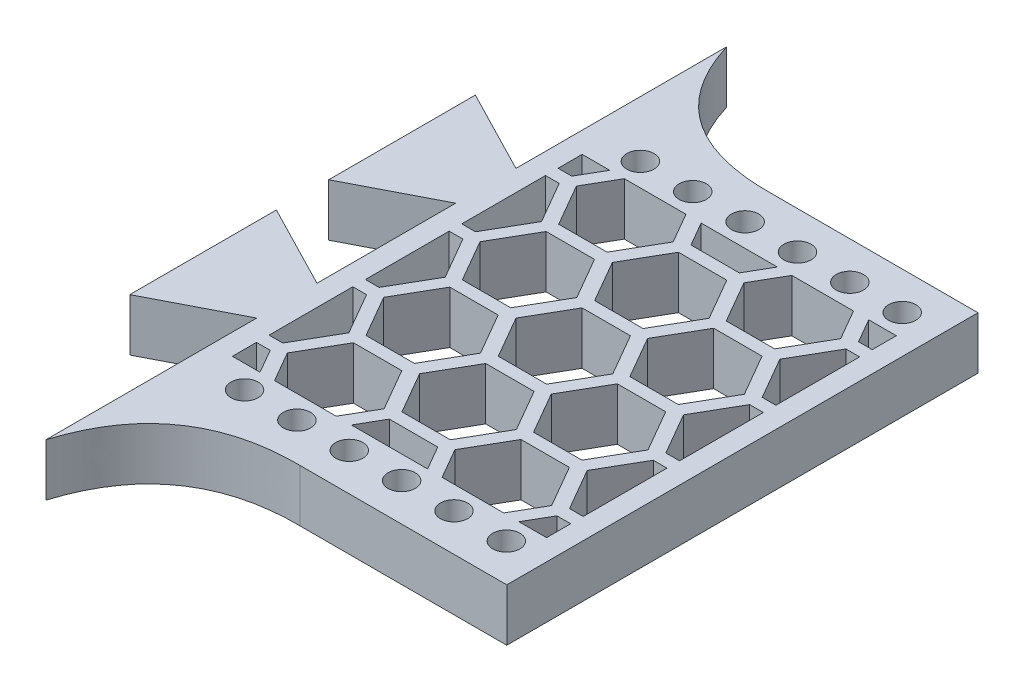
SolidWorks part; units mm, degrees
material "ABS PC"
ref_plane "Front Plane" through (0, 0, 0) normal (0, 0, 1) x (1, 0, 0)
ref_plane "Top Plane" through (0, 0, 0) normal (0, 1, 0) x (1, 0, 0)
ref_plane "Right Plane" through (0, 0, 0) normal (1, 0, 0) x (0, 0, -1)
sketch "Sketch1" plane through (0, 0, 0) normal (0, 1, 0) x (1, 0, 0)
  line L0 (-21.59, -15.7187) -> (-31.75, -20.955)
  line L1 (21.59, -28.575) -> (-21.59, -28.575)
  line L2 (21.59, -28.575) -> (21.59, 28.575)
  line L3 (21.59, 28.575) -> (-21.59, 28.575)
  line L4 (-21.59, -28.575) -> (-21.59, 28.575)
  line L5 (21.59, -28.575) -> (-21.59, 28.575) construction
  line L6 (21.59, 28.575) -> (-21.59, -28.575) construction
  line L7 (-31.75, -20.955) -> (-31.75, -3.175)
  line L8 (-31.75, -3.175) -> (-21.59, -8.4113)
  line L9 (-21.59, 8.4113) -> (-31.75, 3.175)
  line L10 (-31.75, 3.175) -> (-31.75, 20.955)
  line L11 (-31.75, 20.955) -> (-21.59, 15.7187)
  line L12 (-21.59, 15.7187) -> (0, 0) construction
  line L13 (0, 0) -> (-21.59, -15.7187) construction
  line L14 (0, 0) -> (-31.75, 3.175) construction
  line L15 (-31.75, -3.175) -> (0, 0) construction
  line L16 (-21.59, -28.575) -> (-21.59, -41.275)
  line L18 (-21.59, -28.575) -> (-10.9458, -36.6173) construction
  line L19 (0, 0) -> (21.59, 0) construction
  line L20 (-21.59, 28.575) -> (-21.59, 41.275)
  spline S0 degree 2 poles (-21.59, -41.275) (-17.6152, -28.3979) (-3.4579, -28.575) knots 0 0 0 1 1 1
  spline S1 degree 2 poles (-21.59, 41.275) (-17.6152, 28.3979) (-3.4579, 28.575) knots 0 0 0 1 1 1
  point P0 (0, 0)
  point P22 (0, 0)
  point P24 (0, 0)
  point P25 (-3.3106, -29.6861)
  point P26 (0, 0)
  point P27 (-17.0157, -32.0311)
  point P28 (-7.5052, -28.575)
  point P29 (-10.9458, -36.6173)
  point P30 (-6.1522, -28.575)
  point P31 (-3.4579, -28.575)
  dimension "D1" = 57.15
  dimension "D2" = 43.18
  dimension "D3" = 17.78
  dimension "D4" = 11.43
  dimension "D5" = 10.16
  dimension "D6" = 6.35
  dimension "D7" = 12.7
extrude "Boss-Extrude1" add sketch "Sketch1" along normal blind 6.35 contours L8 L7 L0 L4 | L4 L1 L2 L3 | L11 L10 L9 L4 | L16 S0 L1 | S1 L20 L3
sketch "Sketch2" plane through (0, 6.35, 0) normal (0, 1, 0) x (1, 0, 0)
  line L0 (21.59, -28.575) -> (21.59, 28.575) construction
  line L1 (21.59, 28.575) -> (-3.4579, 28.575) construction
  line L2 (21.59, -28.575) -> (-3.4579, -28.575) construction
  circle A0 centre (4.2672, 24.003) radius 1.651
  circle A1 centre (4.2672, -24.003) radius 1.651
  circle A2 centre (10.6172, 24.003) radius 1.651
  circle A3 centre (10.6172, -24.003) radius 1.651
  circle A4 centre (16.9672, 24.003) radius 1.651
  circle A5 centre (16.9672, -24.003) radius 1.651
  circle A6 centre (-2.0828, 24.003) radius 1.651
  circle A7 centre (-2.0828, -24.003) radius 1.651
  circle A8 centre (-8.4328, 24.003) radius 1.651
  circle A9 centre (-8.4328, -24.003) radius 1.651
  circle A10 centre (-14.7828, 24.003) radius 1.651
  circle A11 centre (-14.7828, -24.003) radius 1.651
  dimension "D1" = 17.3228
  dimension "D2" = 17.3228
  dimension "D3" = 4.572
  dimension "D4" = 4.572
  dimension "D5" = 3.302
  dimension "D6" = 3
  dimension "D7" = 4
extrude "Cut-Extrude1" cut sketch "Sketch2" against normal through all
sketch "Sketch3" plane through (0, 6.35, 0) normal (0, 1, 0) x (1, 0, 0)
  line L0 (26.1859, 0) -> (23.2529, 5.08)
  line L1 (5.8659, 0) -> (2.9329, 5.08)
  line L2 (2.9329, 5.08) -> (-2.9329, 5.08)
  line L3 (-2.9329, 5.08) -> (-5.8659, 0)
  line L4 (-5.8659, 0) -> (-2.9329, -5.08)
  line L5 (-2.9329, -5.08) -> (2.9329, -5.08)
  line L6 (2.9329, -5.08) -> (5.8659, 0)
  line L7 (23.2529, 5.08) -> (17.3871, 5.08)
  line L8 (17.3871, 5.08) -> (14.4541, 0)
  line L9 (14.4541, 0) -> (17.3871, -5.08)
  line L10 (17.3871, -5.08) -> (23.2529, -5.08)
  line L11 (23.2529, -5.08) -> (26.1859, 0)
  line L12 (26.1859, 11.684) -> (23.2529, 16.764)
  line L13 (23.2529, 16.764) -> (17.3871, 16.764)
  line L14 (17.3871, 16.764) -> (14.4541, 11.684)
  line L15 (14.4541, 11.684) -> (17.3871, 6.604)
  line L16 (17.3871, 6.604) -> (23.2529, 6.604)
  line L17 (23.2529, 6.604) -> (26.1859, 11.684)
  line L18 (26.1859, 23.368) -> (23.2529, 28.448)
  line L19 (23.2529, 28.448) -> (17.3871, 28.448)
  line L20 (17.3871, 28.448) -> (14.4541, 23.368)
  line L21 (14.4541, 23.368) -> (17.3871, 18.288)
  line L22 (17.3871, 18.288) -> (23.2529, 18.288)
  line L23 (23.2529, 18.288) -> (26.1859, 23.368)
  line L24 (5.8659, 11.684) -> (2.9329, 16.764)
  line L25 (2.9329, 16.764) -> (-2.9329, 16.764)
  line L26 (-2.9329, 16.764) -> (-5.8659, 11.684)
  line L27 (-5.8659, 11.684) -> (-2.9329, 6.604)
  line L28 (-2.9329, 6.604) -> (2.9329, 6.604)
  line L29 (2.9329, 6.604) -> (5.8659, 11.684)
  line L30 (5.8659, 23.368) -> (2.9329, 28.448)
  line L31 (2.9329, 28.448) -> (-2.9329, 28.448)
  line L32 (-2.9329, 28.448) -> (-5.8659, 23.368)
  line L33 (-5.8659, 23.368) -> (-2.9329, 18.288)
  line L34 (-2.9329, 18.288) -> (2.9329, 18.288)
  line L35 (2.9329, 18.288) -> (5.8659, 23.368)
  line L36 (-14.4541, 0) -> (-17.3871, 5.08)
  line L37 (-17.3871, 5.08) -> (-23.2529, 5.08)
  line L38 (-23.2529, 5.08) -> (-26.1859, 0)
  line L39 (-26.1859, 0) -> (-23.2529, -5.08)
  line L40 (-23.2529, -5.08) -> (-17.3871, -5.08)
  line L41 (-17.3871, -5.08) -> (-14.4541, 0)
  line L42 (-14.4541, -11.684) -> (-17.3871, -6.604)
  line L43 (-17.3871, -6.604) -> (-23.2529, -6.604)
  line L44 (-23.2529, -6.604) -> (-26.1859, -11.684)
  line L45 (-26.1859, -11.684) -> (-23.2529, -16.764)
  line L46 (-23.2529, -16.764) -> (-17.3871, -16.764)
  line L47 (-17.3871, -16.764) -> (-14.4541, -11.684)
  line L48 (-14.4541, -23.368) -> (-17.3871, -18.288)
  line L49 (-17.3871, -18.288) -> (-23.2529, -18.288)
  line L50 (-23.2529, -18.288) -> (-26.1859, -23.368)
  line L51 (-26.1859, -23.368) -> (-23.2529, -28.448)
  line L52 (-23.2529, -28.448) -> (-17.3871, -28.448)
  line L53 (-17.3871, -28.448) -> (-14.4541, -23.368)
  line L54 (5.8659, -11.684) -> (2.9329, -6.604)
  line L55 (2.9329, -6.604) -> (-2.9329, -6.604)
  line L56 (-2.9329, -6.604) -> (-5.8659, -11.684)
  line L57 (-5.8659, -11.684) -> (-2.9329, -16.764)
  line L58 (-2.9329, -16.764) -> (2.9329, -16.764)
  line L59 (2.9329, -16.764) -> (5.8659, -11.684)
  line L60 (5.8659, -23.368) -> (2.9329, -18.288)
  line L61 (2.9329, -18.288) -> (-2.9329, -18.288)
  line L62 (-2.9329, -18.288) -> (-5.8659, -23.368)
  line L63 (-5.8659, -23.368) -> (-2.9329, -28.448)
  line L64 (-2.9329, -28.448) -> (2.9329, -28.448)
  line L65 (2.9329, -28.448) -> (5.8659, -23.368)
  line L66 (-14.4541, 11.684) -> (-17.3871, 16.764)
  line L67 (-17.3871, 16.764) -> (-23.2529, 16.764)
  line L68 (-23.2529, 16.764) -> (-26.1859, 11.684)
  line L69 (-26.1859, 11.684) -> (-23.2529, 6.604)
  line L70 (-23.2529, 6.604) -> (-17.3871, 6.604)
  line L71 (-17.3871, 6.604) -> (-14.4541, 11.684)
  line L72 (-14.4541, 23.368) -> (-17.3871, 28.448)
  line L73 (-17.3871, 28.448) -> (-23.2529, 28.448)
  line L74 (-23.2529, 28.448) -> (-26.1859, 23.368)
  line L75 (-26.1859, 23.368) -> (-23.2529, 18.288)
  line L76 (-23.2529, 18.288) -> (-17.3871, 18.288)
  line L77 (-17.3871, 18.288) -> (-14.4541, 23.368)
  line L78 (26.1859, -11.684) -> (23.2529, -6.604)
  line L79 (15.9845, -17.526) -> (13.0516, -12.446)
  line L80 (13.0516, -12.446) -> (7.1857, -12.446)
  line L81 (7.1857, -12.446) -> (4.2528, -17.526)
  line L82 (4.2528, -17.526) -> (7.1857, -22.606)
  line L83 (7.1857, -22.606) -> (13.0516, -22.606)
  line L84 (13.0516, -22.606) -> (15.9845, -17.526)
  line L85 (23.2529, -6.604) -> (17.3871, -6.604)
  line L86 (17.3871, -6.604) -> (14.4541, -11.684)
  line L87 (14.4541, -11.684) -> (17.3871, -16.764)
  line L88 (17.3871, -16.764) -> (23.2529, -16.764)
  line L89 (23.2529, -16.764) -> (26.1859, -11.684)
  line L90 (26.1859, -23.368) -> (23.2529, -18.288)
  line L91 (23.2529, -18.288) -> (17.3871, -18.288)
  line L92 (17.3871, -18.288) -> (14.4541, -23.368)
  line L93 (14.4541, -23.368) -> (17.3871, -28.448)
  line L94 (17.3871, -28.448) -> (23.2529, -28.448)
  line L95 (23.2529, -28.448) -> (26.1859, -23.368)
  line L96 (-4.3355, -17.526) -> (-7.2684, -12.446)
  line L97 (-13.1343, -12.446) -> (-16.0672, -17.526)
  line L98 (-16.0672, -17.526) -> (-13.1343, -22.606)
  line L99 (-7.2684, -22.606) -> (-4.3355, -17.526)
  line L100 (-7.2684, -12.446) -> (-13.1343, -12.446)
  line L101 (-13.1343, -22.606) -> (-7.2684, -22.606)
  line L102 (-4.3355, -5.842) -> (-7.2684, -0.762)
  line L103 (-13.1343, -0.762) -> (-16.0672, -5.842)
  line L104 (-16.0672, -5.842) -> (-13.1343, -10.922)
  line L105 (-7.2684, -10.922) -> (-4.3355, -5.842)
  line L106 (-7.2684, -0.762) -> (-13.1343, -0.762)
  line L107 (-13.1343, -10.922) -> (-7.2684, -10.922)
  line L108 (-4.3355, 5.842) -> (-7.2684, 10.922)
  line L109 (-13.1343, 10.922) -> (-16.0672, 5.842)
  line L110 (-16.0672, 5.842) -> (-13.1343, 0.762)
  line L111 (-7.2684, 0.762) -> (-4.3355, 5.842)
  line L112 (-7.2684, 10.922) -> (-13.1343, 10.922)
  line L113 (-13.1343, 0.762) -> (-7.2684, 0.762)
  line L114 (-4.3355, 17.526) -> (-7.2684, 22.606)
  line L115 (-13.1343, 22.606) -> (-16.0672, 17.526)
  line L116 (-16.0672, 17.526) -> (-13.1343, 12.446)
  line L117 (-7.2684, 12.446) -> (-4.3355, 17.526)
  line L118 (-7.2684, 22.606) -> (-13.1343, 22.606)
  line L119 (-13.1343, 12.446) -> (-7.2684, 12.446)
  line L120 (15.9845, -5.842) -> (13.0516, -0.762)
  line L121 (7.1857, -0.762) -> (4.2528, -5.842)
  line L122 (4.2528, -5.842) -> (7.1857, -10.922)
  line L123 (13.0516, -10.922) -> (15.9845, -5.842)
  line L124 (13.0516, -0.762) -> (7.1857, -0.762)
  line L125 (7.1857, -10.922) -> (13.0516, -10.922)
  line L126 (15.9845, 5.842) -> (13.0516, 10.922)
  line L127 (7.1857, 10.922) -> (4.2528, 5.842)
  line L128 (4.2528, 5.842) -> (7.1857, 0.762)
  line L129 (13.0516, 0.762) -> (15.9845, 5.842)
  line L130 (13.0516, 10.922) -> (7.1857, 10.922)
  line L131 (7.1857, 0.762) -> (13.0516, 0.762)
  line L132 (15.9845, 17.526) -> (13.0516, 22.606)
  line L133 (7.1857, 22.606) -> (4.2528, 17.526)
  line L134 (4.2528, 17.526) -> (7.1857, 12.446)
  line L135 (13.0516, 12.446) -> (15.9845, 17.526)
  line L136 (13.0516, 22.606) -> (7.1857, 22.606)
  line L137 (7.1857, 12.446) -> (13.0516, 12.446)
  line L138 (-19.05, 21.209) -> (19.05, 21.209)
  line L139 (19.05, 21.209) -> (19.05, -21.209)
  line L140 (19.05, -21.209) -> (-19.05, -21.209)
  line L141 (-19.05, -21.209) -> (-19.05, 21.209)
  line L142 (-21.59, 15.7187) -> (-21.59, 41.275) construction
  line L143 (21.59, -28.575) -> (21.59, 28.575) construction
  circle A0 centre (0, 0) radius 5.08 construction
  circle A1 centre (20.32, 0) radius 5.08 construction
  circle A2 centre (20.32, 11.684) radius 5.08 construction
  circle A3 centre (20.32, 23.368) radius 5.08 construction
  circle A4 centre (0, 11.684) radius 5.08 construction
  circle A5 centre (0, 23.368) radius 5.08 construction
  circle A6 centre (-20.32, 0) radius 5.08 construction
  circle A7 centre (-20.32, -11.684) radius 5.08 construction
  circle A8 centre (-20.32, -23.368) radius 5.08 construction
  circle A9 centre (0, -11.684) radius 5.08 construction
  circle A10 centre (0, -23.368) radius 5.08 construction
  circle A11 centre (-20.32, 11.684) radius 5.08 construction
  circle A12 centre (-20.32, 23.368) radius 5.08 construction
  circle A13 centre (10.1186, -17.526) radius 5.08 construction
  circle A14 centre (20.32, -11.684) radius 5.08 construction
  circle A15 centre (20.32, -23.368) radius 5.08 construction
  circle A16 centre (-10.2014, -17.526) radius 5.08 construction
  circle A17 centre (-10.2014, -5.842) radius 5.08 construction
  circle A18 centre (-10.2014, 5.842) radius 5.08 construction
  circle A19 centre (-10.2014, 17.526) radius 5.08 construction
  circle A20 centre (10.1186, -5.842) radius 5.08 construction
  circle A21 centre (10.1186, 5.842) radius 5.08 construction
  circle A22 centre (10.1186, 17.526) radius 5.08 construction
  circle A23 centre (-2.0828, -24.003) radius 1.651 construction
  circle A24 centre (16.9672, 24.003) radius 1.651 construction
  dimension "D1" = 10.16
  dimension "D5" = 1.524
  dimension "D6" = 1.524
  dimension "D8" = 2.54
  dimension "D9" = 2.794
  dimension "D10" = 2.54
  dimension "D11" = 2.794
  dimension "D2" = 2
  dimension "D15" = 3
  dimension "D3" = 2
  dimension "D4" = 3
  dimension "D14" = 3
  dimension "D13" = 3
  dimension "D7" = 2
  dimension "D12" = 4
extrude "Cut-Extrude2" cut sketch "Sketch3" against normal through all contours L141 L76 L77 L138 | L138 L115 L116 L119 L117 L114 | L141 L70 L71 L66 L67 | L110 L113 L111 L108 L112 L109 | L141 L40 L41 L36 L37 | L104 L107 L105 L102 L106 L103 | L141 L46 L47 L42 L43 | L140 L99 L96 L100 L97 L98 | L141 L140 L48 L49 | L140 L60 L61 L62 | L58 L59 L54 L55 L56 L57 | L5 L6 L1 L2 L3 L4 | L28 L29 L24 L25 L26 L27 | L138 L33 L34 L35 | L138 L133 L134 L137 L135 L132 | L139 L138 L21 L22 | L139 L13 L14 L15 L16 | L128 L131 L129 L126 L130 L127 | L139 L7 L8 L9 L10 | L122 L125 L123 L120 L124 L121 | L139 L85 L86 L87 L88 | L140 L84 L79 L80 L81 L82 | L140 L139 L91 L92
